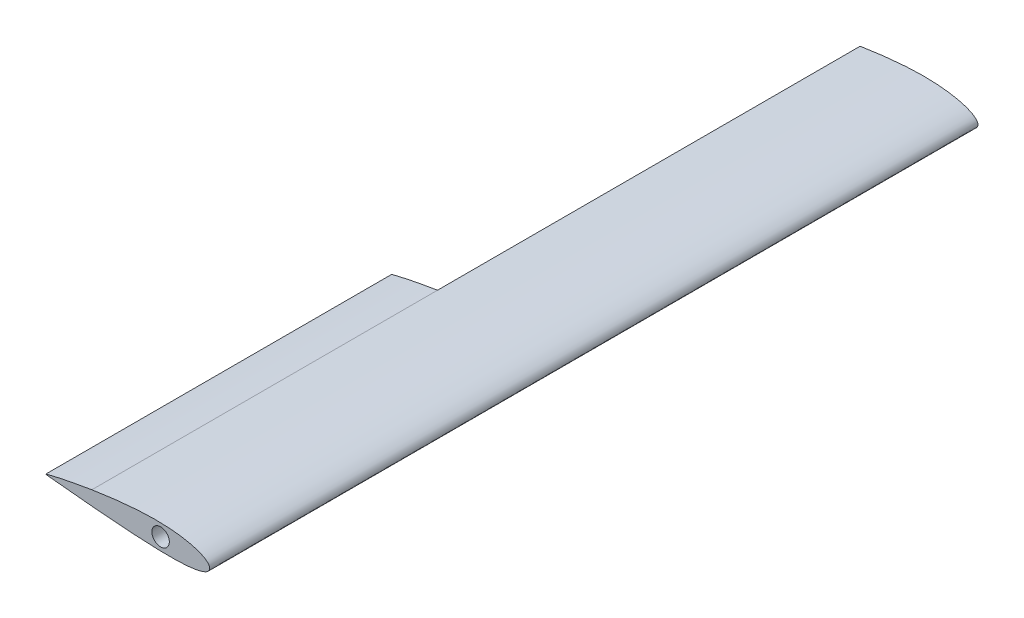
SolidWorks part; units mm, degrees
ref_plane "Front Plane" through (0, 0, 0) normal (0, 0, 1) x (1, 0, 0)
ref_plane "Top Plane" through (0, 0, 0) normal (0, 1, 0) x (1, 0, 0)
ref_plane "Right Plane" through (0, 0, 0) normal (1, 0, 0) x (0, 0, -1)
sketch "Sketch1" plane through (0, 0, 0) normal (0, 0, 1) x (1, 0, 0)
  line L0 (-171.846, 13.8024) -> (-171.846, -6.8859)
  spline S0 degree 3 poles (-171.846, 13.8024) (-169.6872, 14.1466) (-164.5979, 14.958) (-156.4872, 16.1423) (-147.4603, 17.3704) (-138.2511, 18.5099) (-128.9173, 19.5455) (-119.5168, 20.4576) (-110.1086, 21.229) (-100.7387, 21.8426) (-91.4486, 22.2882) (-82.2958, 22.496) (-73.3548, 22.4639) (-64.7028, 22.1871) (-56.3979, 21.6678) (-48.4959, 20.9122) (-41.0494, 19.9314) (-34.1075, 18.7407) (-27.7153, 17.3594) (-21.9133, 15.8098) (-16.7367, 14.1166) (-12.2152, 12.3056) (-8.3725, 10.4021) (-5.2252, 8.4289) (-2.7832, 6.4015) (-1.0522, 4.3226) (-0.0567, 2.1725) (0.1298, -0.013) (-0.4851, -2.1166) (-1.8739, -4.0278) (-3.9517, -5.7341) (-6.6937, -7.2673) (-10.0887, -8.6373) (-14.1208, -9.8444) (-18.7681, -10.8855) (-24.0034, -11.7578) (-29.7957, -12.4602) (-36.1108, -12.9938) (-42.9122, -13.363) (-50.1607, -13.5749) (-57.8154, -13.64) (-65.8334, -13.5713) (-74.17, -13.3843) (-82.7787, -13.0969) (-91.6286, -12.7253) (-100.6831, -12.2947) (-109.8865, -11.7662) (-119.1666, -11.1621) (-128.454, -10.4982) (-137.6926, -9.7903) (-146.8261, -9.0527) (-155.7985, -8.2977) (-164.1209, -7.5767) (-169.4455, -7.1006) (-171.846, -6.8859) knots 0 0 0 0 0.018424 0.043434 0.06908 0.095203 0.12164 0.148227 0.1748 0.201195 0.227364 0.253182 0.278347 0.30271 0.326128 0.348467 0.3696 0.389416 0.407811 0.424699 0.440008 0.453688 0.465715 0.476104 0.484928 0.49236 0.49873 0.504587 0.510443 0.516804 0.524199 0.532941 0.543186 0.554996 0.568376 0.583299 0.599709 0.617539 0.636704 0.657109 0.678651 0.701217 0.724685 0.748928 0.773811 0.799338 0.825326 0.851504 0.877716 0.9038 0.929596 0.954944 0.979688 1 1 1 1
extrude "Boss-Extrude1" add sketch "Sketch1" against normal blind 1120
sketch "Sketch2" plane through (0, 0, 0) normal (0, 0, 1) x (1, 0, 0)
  line L0 (-171.846, 13.8024) -> (-171.846, -6.8859)
  line L1 (-238.675, 0.3812) -> (-238.675, -0.3751)
  spline S0 degree 3 poles (-171.846, 13.8024) (-172.5253, 13.696) (-175.9331, 13.1622) (-181.9297, 12.1426) (-189.6926, 10.7734) (-197.0148, 9.4101) (-203.8537, 8.0798) (-210.1682, 6.8003) (-215.9209, 5.5913) (-221.0778, 4.4715) (-225.609, 3.4587) (-229.488, 2.5698) (-232.6924, 1.8199) (-235.2039, 1.2222) (-237.0081, 0.7872) (-238.0864, 0.525) (-238.5621, 0.4088) (-238.675, 0.3812) knots 0 0 0 0 0.030252 0.151774 0.267626 0.37709 0.479485 0.574175 0.66057 0.73813 0.806369 0.864859 0.913229 0.951173 0.978451 0.994887 1 1 1 1
  spline S1 degree 3 poles (-171.846, -6.8859) (-172.2799, -6.8474) (-175.4408, -6.5664) (-181.2026, -6.039) (-188.9905, -5.3185) (-196.3547, -4.624) (-203.2487, -3.9637) (-209.6287, -3.3428) (-215.4538, -2.7672) (-220.6864, -2.2426) (-225.2928, -1.7737) (-229.243, -1.3675) (-232.5108, -1.0239) (-235.0757, -0.761) (-236.9188, -0.5487) (-238.0316, -0.4591) (-238.5336, -0.3746) (-238.6667, -0.3751) (-238.675, -0.3751) knots 0 0 0 0 0.019463 0.141781 0.258505 0.3689 0.472262 0.567931 0.655294 0.733785 0.802892 0.862162 0.911205 0.949694 0.977373 0.994054 0.999628 1 1 1 1
extrude "Boss-Extrude2" add sketch "Sketch2" against normal blind 504
sketch "Sketch3" plane through (0, 0, 0) normal (0, 0, 1) x (1, 0, 0)
  circle A0 centre (-71.603, 4.475) radius 12.7
extrude "Cut-Extrude2" cut sketch "Sketch3" against normal blind 800
